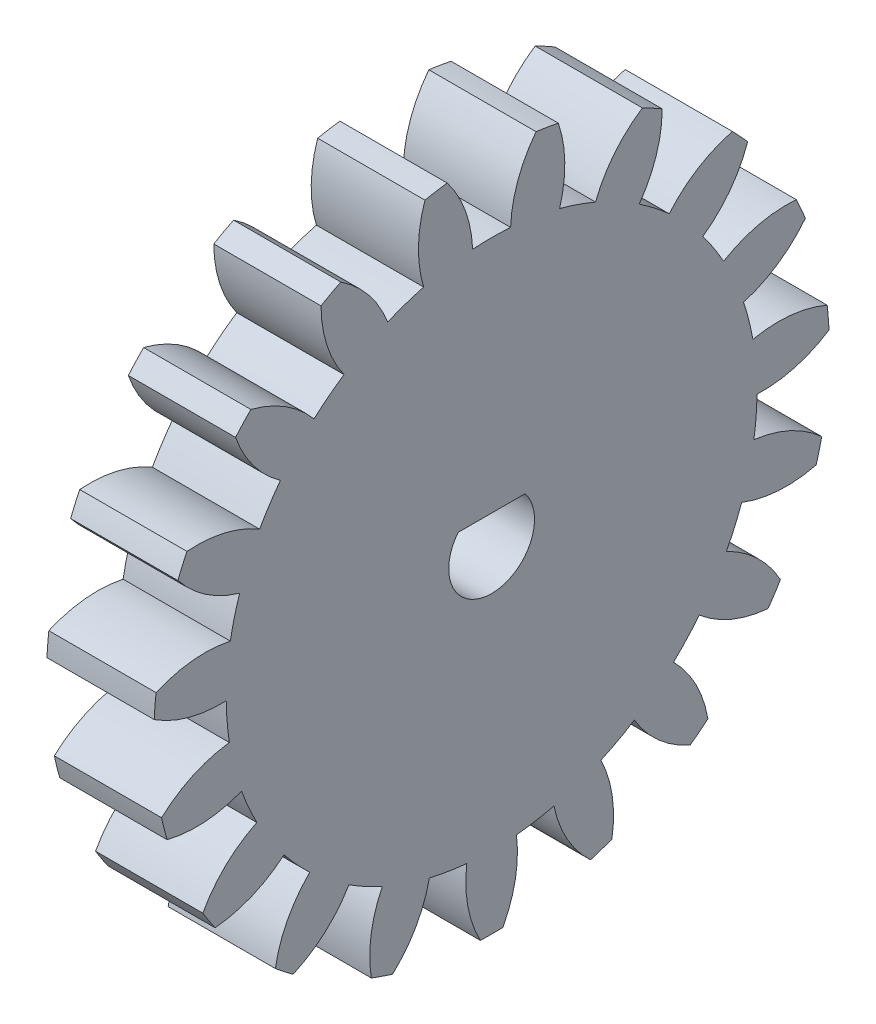
SolidWorks part; units mm, degrees
ref_plane "Plane1" through (0, 0, 0) normal (0, 0, 1) x (1, 0, 0)
ref_plane "Plane2" through (0, 0, 0) normal (0, 1, 0) x (1, 0, 0)
ref_plane "Plane3" through (0, 0, 0) normal (1, 0, 0) x (0, 0, -1)
sketch "HoldingSke" plane through (0, 0, 0) normal (0, 1, 0) x (1, 0, 0)
  line L0 (0, 0) -> (0.6303, -0.217)
  line L1 (-15, 0) -> (100, 0) construction
  line L2 (0, 0) -> (-2.1039, 2.3779)
  line L3 (0, 0) -> (-11.863, 4.5341)
  line L4 (0, 0) -> (8.1655, 2.8116)
  line L5 (0, 0) -> (-46.8476, -17.4728)
  line L6 (0, 0) -> (-4.1448, -2.7965)
  line L7 (-2.1039, 2.3779) -> (8.6586, 51.2059)
  line L8 (-76.2, 54.61) -> (-76.1, 54.61)
  line L9 (-67.7845, 28.3722) -> (-49.3413, 33.142)
  line L10 (-76.2, 71.12) -> (104.1128, 71.12)
  line L11 (0, 0) -> (-5, 0)
  line L12 (-76.2, 101.6) -> (-76.147, 101.6)
  line L13 (24.9733, 27.94) -> (52.9518, 28.4284)
  line L14 (24.9733, 27.94) -> (24.9743, 27.94)
  line L15 (24.9733, 27.94) -> (100.4006, 29.5858)
  line L16 (-63.627, -1.5) -> (-12.827, -1.5)
  circle A0 centre (0, 0) radius 0.4
  circle A1 centre (0, 0) radius 12.374
  circle A2 centre (0, 0) radius 37.5
  circle A3 centre (0, 0) radius 0.4
  dimension "MHD" = 24.748
  dimension "Hub_dia" = 75
  dimension "Bore" = 0.8
  dimension "MBD" = 0.8
  dimension "Num_teeth" = 19
  dimension "Pitch" = 0.6667
  dimension "Overall_len" = 50
  dimension "Show_teeth" = 19
  dimension "Thickness" = 5
  dimension "OAL" = 50.0001
  dimension "T_dim" = 0.1
  dimension "Ap" = 14.5
  dimension "H" = 19.05
  dimension "Pitch_radius" = 180.3128
  dimension "Width" = 5
  dimension "Backlash" = 0.053
  dimension "Addendum_fac" = 1
  dimension "Dedendum_fac" = 1.25
  dimension "Clearance_fac" = 0.25
  dimension "Dedendum_add" = 0.001
  dimension "Module" = 1.5
sketch "BasProSke" plane through (0, 0, 0) normal (0, 1, 0) x (1, 0, 0)
  line L0 (-10, 0) -> (60, 0) construction
  line L1 (0, 0) -> (0, 15.75)
  line L2 (0, 0) -> (5, 0)
  line L3 (5, 0) -> (5, 15.75)
  line L4 (5, 15.75) -> (0, 15.75)
  dimension "Thickness" = 5
  dimension "Diameter" = 31.5
revolve "Base-Revolve" add sketch "BasProSke" angle 360 about L0
sketch "TooCutSke" plane through (0, 0, 0) normal (1, 0, 0) x (0, 0, -1)
  line L1 (0, 0) -> (0, 107) construction
  line L2 (0, 0) -> (-1.2695, 14.1933) construction
  line L3 (0, 0) -> (-4.6774, 28.0298) construction
  line L4 (-1.2695, 14.1933) -> (-2.3387, 14.0149) construction
  arc A0 (0.8852, 12.3423) -> (-0.8852, 12.3423) centre (0, 0) ccw
  arc A1 (2.0907, 15.6362) -> (-2.0907, 15.6362) centre (0, 0) ccw
  circle A2 centre (0, 0) radius 14.25 construction
  circle A3 centre (0, 0) radius 13.7961 construction
  arc A4 (-0.8852, 12.3423) -> (-2.0907, 15.6362) centre (-6.5811, 12.1253) ccw
  arc A5 (2.0907, 15.6362) -> (0.8852, 12.3423) centre (6.5811, 12.1253) ccw
  dimension "Root_dia" = 24.748
  dimension "Overcut_dia" = 31.5508
  dimension "Pitch_dia" = 28.5
  dimension "Base_dia" = 27.5922
  dimension "Flank_rad" = 5.7
  dimension "Half_ang" = 9.474
  dimension "Half_CT" = 1.084
extrude "ToothCut" cut sketch "TooCutSke" along normal through all
fillet "Breaks" [suppressed] radius 0.03
fillet "RootFillets" [suppressed] radius 0.376
pattern_circular "TeethCuts" count 19 every 18.947 about axis through (-10, 0, 0) along (1, 0, 0) of "ToothCut", "RootFillets", "Breaks"
sketch "HubNeaOneSke" plane through (0, 0, 0) normal (-1, 0, 0) x (0, 0, 1)
  circle A0 centre (0, 0) radius 12.374
  dimension "Diameter" = 24.748
extrude "HubNearOne" [suppressed] add sketch "HubNeaOneSke" along normal blind 45.0001
sketch "HubNeaBotSke" plane through (0, 0, 0) normal (-1, 0, 0) x (0, 0, 1)
  circle A0 centre (0, 0) radius 12.374
  dimension "Diameter" = 24.748
extrude "HubNearBoth" [suppressed] add sketch "HubNeaBotSke" along normal blind 22.5
ref_plane "FarPln" through (5, 0, 0) normal (1, 0, 0) x (0, 0, -1)
sketch "HubFarSke" plane through (5, 0, 0) normal (1, 0, 0) x (0, 0, -1)
  circle A0 centre (0, 0) radius 12.374
  dimension "Diameter" = 24.748
extrude "HubFar" [suppressed] add sketch "HubFarSke" along normal blind 22.5
sketch "BorSke" plane through (0, 0, 0) normal (1, 0, 0) x (0, 0, -1)
  circle A0 centre (0, 0) radius 0.4
  dimension "Diameter" = 0.8
extrude "Bore" cut sketch "BorSke" along normal mid plane 100.0001
sketch "KeySke" plane through (0, 0, 0) normal (1, 0, 0) x (0, 0, -1)
  line L0 (-0.05, 0) -> (-0.05, 0.5)
  line L1 (-0.05, 0.5) -> (0.05, 0.5)
  line L2 (0.05, 0.5) -> (0.05, 0)
  line L3 (0, 0) -> (0, 34) construction
  line L4 (-0.05, 0) -> (0.05, 0)
  dimension "Offset" = 0.5
  dimension "Width" = 0.1
extrude "Keyway" [suppressed] cut sketch "KeySke" along normal mid plane 100.0001
pattern_circular "Keyway2" [suppressed] count 2 every 90 about axis through (-10, 0, 0) along (1, 0, 0)
sketch "Sketch1" plane through (5, 0, 0) normal (1, 0, 0) x (0, 0, -1)
  line L0 (-1.5606, 1.2508) -> (1.5606, 1.2508)
  circle A0 centre (0, 0) radius 2
extrude "Cut-Extrude1" cut sketch "Sketch1" against normal through all contours L0 A0
equation "' \"Module@HoldingSke\" = 6.35"
equation "' \"Num_teeth@HoldingSke\" = 12"
equation "' \"Ap@HoldingSke\" =  20"
equation "' \"Ap@HoldingSke\" = 20"
equation "' \"Width@HoldingSke\" = 0.5 * 25.4"
equation "' \"Hub_dia@HoldingSke\"= 1 * 25.4"
equation "' \"Hub_dia@HoldingSke\" = 1 * 25.4"
equation "' \"Overall_len@HoldingSke\" = 1.0 * 25.4"
equation "' \"Bore@HoldingSke\" = 0.75 * 25.4"
equation "' \"T_dim@HoldingSke\" = 0.1 * 25.4"
equation "' \"Width@KeySke\" = 0.25 * 25.4"
equation "' \"Show_teeth@HoldingSke\" = 13"
equation "' \"Backlash@HoldingSke\" = 0.009 * 25.4"
equation "' \"Addendum_fac@HoldingSke\" = 1.0"
equation "' \"Dedendum_fac@HoldingSke\" = 1.25"
equation "' \"Dedendum_add@HoldingSke\" = 0.00005 * 25.4"
equation "' \"Clearance_fac@HoldingSke\" = 0.25"
equation "\"Pitch@HoldingSke\" = 1 / \"Module@HoldingSke\""
equation "\"Overcut_dia@TooCutSke\" = (\"Num_teeth@HoldingSke\" + 2 * \"Addendum_fac@HoldingSke\") / \"Pitch@HoldingSke\" + 0.002 * 25.4"
equation "\"Pitch_dia@TooCutSke\" = \"Num_teeth@HoldingSke\" / \"Pitch@HoldingSke\""
equation "\"Base_dia@TooCutSke\" = \"Num_teeth@HoldingSke\" / \"Pitch@HoldingSke\" * cos((\"Ap@HoldingSke\"  * 3.14159265 / 180))"
equation "\"Root_dia@TooCutSke\" = (\"Num_teeth@HoldingSke\" + 2) / \"Pitch@HoldingSke\" - 2 * (\"Addendum_fac@HoldingSke\" + \"Dedendum_fac@HoldingSke\") / \"Pitch@HoldingSke\" - \"Dedendum_add@HoldingSke\" * 2"
equation "\"Half_ang@TooCutSke\" = 180 / \"Num_teeth@HoldingSke\""
equation "\"Half_CT@TooCutSke\" = \"Num_teeth@HoldingSke\" / \"Pitch@HoldingSke\" * sin((3.14159265 / 2 / \"Num_teeth@HoldingSke\")) / 2 - 7 * \"Backlash@HoldingSke\" / 4"
equation "\"Flank_rad@TooCutSke\" = \"Num_teeth@HoldingSke\" / \"Pitch@HoldingSke\" / 5"
equation "\"Radius@RootFillets\" = \"Clearance_fac@HoldingSke\" / \"Pitch@HoldingSke\" + \"Dedendum_add@HoldingSke\""
equation "\"Break_rad@Breaks\" = 0.02 / \"Pitch@HoldingSke\""
equation "\"Thickness@HoldingSke\" = \"Width@HoldingSke\""
equation "\"OAL@HoldingSke\" = \"Thickness@HoldingSke\""
equation "\"MHD@HoldingSke\" = (\"Num_teeth@HoldingSke\" + 2) / \"Pitch@HoldingSke\" - 2 * (\"Addendum_fac@HoldingSke\" + \"Dedendum_fac@HoldingSke\")  / \"Pitch@HoldingSke\" - \"Dedendum_add@HoldingSke\" * 2"
equation "\"MBD@HoldingSke\" = (\"Num_teeth@HoldingSke\" + 2) / \"Pitch@HoldingSke\" - 2 * (\"Addendum_fac@HoldingSke\" + \"Dedendum_fac@HoldingSke\")  / \"Pitch@HoldingSke\" - \"Dedendum_add@HoldingSke\" * 2 - 0.002 * 25.4"
equation "\"MHD@HoldingSke\" = ((sgn( \"MHD@HoldingSke\" - \"Hub_dia@HoldingSke\" )-1)*( \"MHD@HoldingSke\" - \"Hub_dia@HoldingSke\" ))/-2+ \"Hub_dia@HoldingSke\""
equation "\"MBD@HoldingSke\" = ((sgn( \"MBD@HoldingSke\" - \"Bore@HoldingSke\" )-1)*( \"MBD@HoldingSke\" - \"Bore@HoldingSke\" ))/-2+ \"Bore@HoldingSke\""
equation "\"OAL@HoldingSke\" = ((sgn( \"OAL@HoldingSke\" - \"Overall_len@HoldingSke\" )+1)*( \"OAL@HoldingSke\" - \"Overall_len@HoldingSke\" ))/2 + \"Overall_len@HoldingSke\" + 0.000002 * 25.4"
equation "\"Num_teeth@TeethCuts\" = int( \"Show_teeth@HoldingSke\" ) + 1"
equation "\"Num_teeth@TeethCuts\" = ((sgn( \"Num_teeth@TeethCuts\" - \"Num_teeth@HoldingSke\" )-1)*( \"Num_teeth@TeethCuts\" - \"Num_teeth@HoldingSke\" ))/-2+ \"Num_teeth@HoldingSke\""
equation "\"Num_teeth@TeethCuts\" = ((sgn( \"Num_teeth@TeethCuts\" - 2.0)+1)*( \"Num_teeth@TeethCuts\" - 2.0))/2 +2.0"
equation "\"Angle@TeethCuts\" = 360.0 / \"Num_teeth@HoldingSke\""
equation "\"Diameter@BasProSke\" = (\"Num_teeth@HoldingSke\" + 2 * \"Addendum_fac@HoldingSke\") / \"Pitch@HoldingSke\""
equation "\"Thickness@BasProSke\"  = \"Thickness@HoldingSke\""
equation "' \"Fillet_rad@BasProSke\" =  \"Thickness@HoldingSke\" * 0.05"
equation "' \"Fillet_rad@BasProSke\" = \"Thickness@HoldingSke\" * 0.05"
equation "\"MHD@HoldingSke\" = ((sgn( \"MHD@HoldingSke\" - \"Root_dia@TooCutSke\" )-1)*( \"MHD@HoldingSke\" - \"Root_dia@TooCutSke\" ))/-2+ \"Root_dia@TooCutSke\""
equation "\"Diameter@HubNeaOneSke\" = \"MHD@HoldingSke\""
equation "\"Length@HubNearOne\" = \"OAL@HoldingSke\" - \"Thickness@BasProSke\""
equation "\"Diameter@HubNeaBotSke\" = \"MHD@HoldingSke\""
equation "\"Length@HubNearBoth\" = ( \"OAL@HoldingSke\" - \"Thickness@BasProSke\" ) / 2.0"
equation "\"Thickness@FarPln\" = \"Thickness@BasProSke\""
equation "\"Diameter@HubFarSke\" = \"MHD@HoldingSke\""
equation "\"Length@HubFar\" = ( \"OAL@HoldingSke\" - \"Thickness@BasProSke\" ) / 2.0"
equation "\"Diameter@BorSke\" = \"MBD@HoldingSke\""
equation "\"D1@Bore\" = \"OAL@HoldingSke\" * 2.0"
equation "\"D1@Keyway\" = \"OAL@HoldingSke\" * 2.0"
equation "\"Offset@KeySke\" = \"T_dim@HoldingSke\" + \"MBD@HoldingSke\" / 2.0"
